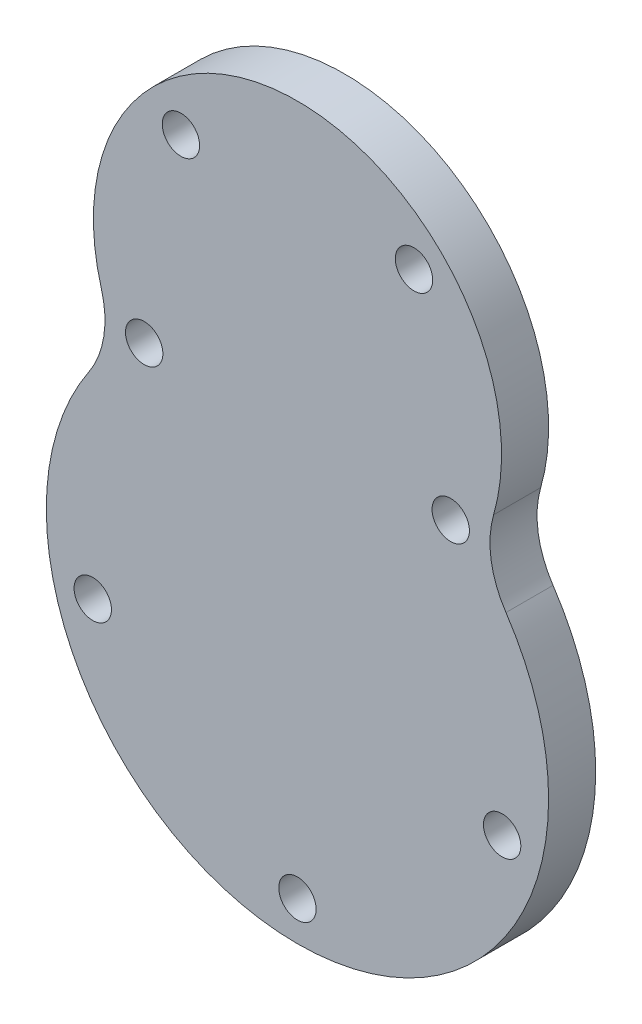
SolidWorks part; units mm, degrees
ref_plane "Plano frontal" through (0, 0, 0) normal (0, 0, 1) x (1, 0, 0)
ref_plane "Plano superior" through (0, 0, 0) normal (0, 1, 0) x (1, 0, 0)
ref_plane "Plano direito" through (0, 0, 0) normal (1, 0, 0) x (0, 0, -1)
sketch "Esboço1" plane through (0, 0, 0) normal (0, 0, 1) x (1, 0, 0)
  arc A0 (24.9934, -7.1647) -> (-24.9934, -7.1647) centre (0, 0) ccw
  arc A1 (-26.5664, -17.161) -> (26.5664, -17.161) centre (0, -35) ccw
  arc A2 (24.9934, -7.1647) -> (26.5664, -17.161) centre (36.5287, -10.4714) ccw
  arc A3 (-24.9934, -7.1647) -> (-26.5664, -17.161) centre (-36.5287, -10.4714) cw
  dimension "D1" = 26
  dimension "D2" = 32
  dimension "D5" = 12
  dimension "D3" = 0
  dimension "D4" = 35
extrude "Ressalto-extrusão1" add sketch "Esboço1" along normal blind 6
sketch "Esboço2" plane through (0, 0, 6) normal (0, 0, 1) x (1, 0, 0)
  line L0 (0, 0) -> (-14.8492, 14.8492) construction
  line L1 (0, 0) -> (14.8492, 14.8492) construction
  line L2 (0, 0) -> (0, 11.9409) construction
  line L3 (0, -35) -> (0, -58.8043) construction
  line L4 (0, -35) -> (-30.1239, -35) construction
  line L5 (0, -35) -> (24.2027, -35) construction
  line L6 (26.08, -41.9881) -> (0, -35) construction
  line L7 (0, -35) -> (-26.08, -41.9881) construction
  circle A0 centre (-14.8492, 14.8492) radius 2.3812
  circle A1 centre (-19.5287, -10.4714) radius 2.3813
  circle A2 centre (14.8492, 14.8492) radius 2.3813
  circle A3 centre (19.5287, -10.4714) radius 2.3813
  circle A4 centre (-26.08, -41.9881) radius 2.3812
  circle A5 centre (0, -62) radius 2.3812
  circle A6 centre (26.08, -41.9881) radius 2.3812
  arc A7 (16.1809, -13.3857) -> (-16.1809, -13.3857) centre (0, 0) ccw construction
  arc A8 (-16.1809, -13.3857) -> (16.1809, -13.3857) centre (0, -35) ccw construction
  arc A10 (-11.4992, -17.5718) -> (-15.0301, -14.6662) centre (0, 0) ccw construction
  circle A12 centre (-36.5287, -10.4714) radius 17 construction
  circle A13 centre (36.5287, -10.4714) radius 17 construction
  dimension "D1" = 4.7625
  dimension "D3" = 42
  dimension "D4" = 54
  dimension "D5" = 34
  dimension "D6" = 34
  dimension "D11" = 0
  dimension "D2" = 21
  dimension "D7" = 0
  dimension "D8" = 17
  dimension "D9" = 0
  dimension "D10" = 17
  dimension "D12" = 27
  dimension "D13" = 27
  dimension "D14" = 27
  dimension "D15" = 15
  dimension "D16" = 15
  dimension "D17" = 45
  dimension "D18" = 45
  dimension "D19" = 21
extrude "Corte-extrusão1" cut sketch "Esboço2" against normal through all
